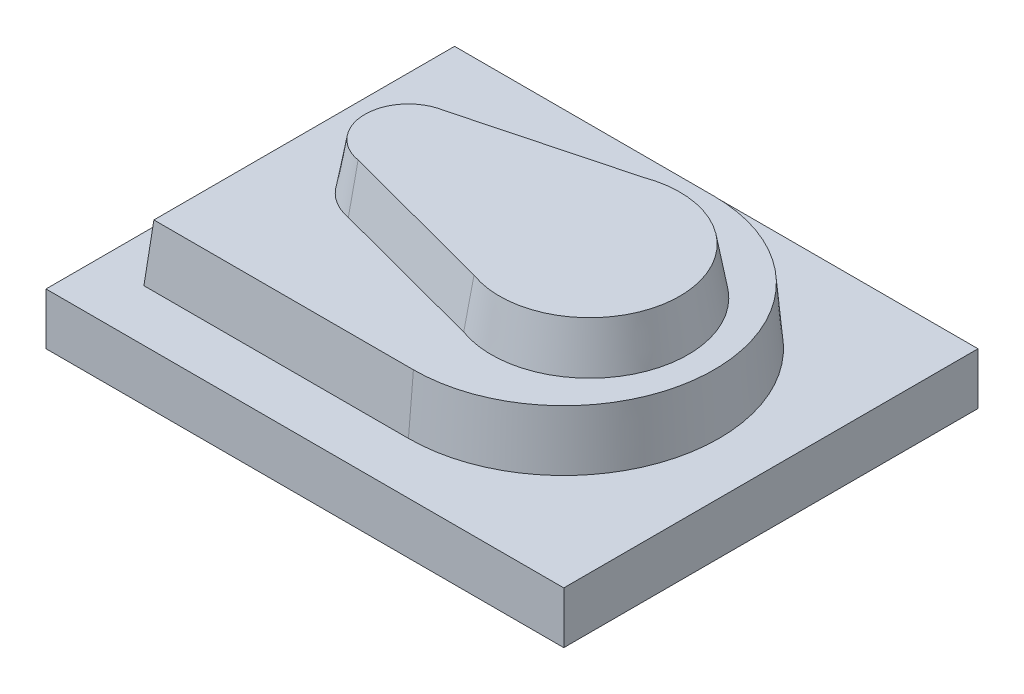
SolidWorks part; units mm, degrees
ref_plane "정면" through (0, 0, 0) normal (0, 0, 1) x (1, 0, 0)
ref_plane "윗면" through (0, 0, 0) normal (0, 1, 0) x (1, 0, 0)
ref_plane "우측면" through (0, 0, 0) normal (1, 0, 0) x (0, 0, -1)
sketch "스케치1" plane through (0, 0, 0) normal (0, 1, 0) x (1, 0, 0)
  line L1 (-50, 40) -> (50, 40)
  line L2 (-50, 40) -> (-50, -40)
  line L3 (-50, -40) -> (50, -40)
  line L4 (50, 40) -> (50, -40)
  line L5 (-50, 40) -> (50, -40) construction
  line L6 (-50, -40) -> (50, 40) construction
  point P0 (0, 0)
  dimension "D1" = 100
  dimension "D2" = 80
extrude "보스-돌출1" add sketch "스케치1" along normal blind 10
sketch "스케치2" plane through (0, 10, 0) normal (0, 1, 0) x (1, 0, 0)
  line L0 (10, 30) -> (-41.0898, 30)
  line L1 (-41.0898, 30) -> (-41.0898, -30)
  line L2 (-41.0898, -30) -> (10, -30)
  line L4 (50, -40) -> (50, 40) construction
  arc A0 (10, 30) -> (10, -30) centre (10, 0) cw
  dimension "D2" = 30
  dimension "D1" = 10
  dimension "D3" = 60
  dimension "D4" = 60
extrude "보스-돌출2" add sketch "스케치2" along normal blind 11 draft 5
ref_plane "평면1" through (0, 21, 0) normal (0, 1, 0) x (1, 0, 0)
sketch "스케치4" plane through (0, 21, 0) normal (0, 1, 0) x (1, 0, 0)
  line L0 (-21.7647, 9.8431) -> (8.5198, 17.8608)
  line L3 (-21.767, -9.8426) -> (8.5427, -17.8691)
  line L4 (-50, 40) -> (-50, -40) construction
  arc A4 (-21.767, -9.8426) -> (-21.7647, 9.8431) centre (-20, 0) cw
  arc A5 (8.5198, 17.8608) -> (8.5427, -17.8691) centre (15, 0) cw
  point P9 (8.5198, -17.8757)
  point P10 (-21.7647, 9.8431)
  point P11 (-21.7647, -9.8426)
  point P12 (8.5198, -17.8691)
  dimension "D1" = 10
  dimension "D2" = 19
  dimension "D3" = 30
  dimension "D4" = 35
extrude "보스-돌출3" add sketch "스케치4" along normal blind 9 draft 10 contours L3 A5 L0 A4
ref_plane "평면3" through (0, 0, 0) normal (0, 0, 1) x (1, 0, 0)
sketch "스케치5" plane through (0, 0, 0) normal (0, 0, 1) x (1, 0, 0)
  arc A0 (-14.7171, 74.7841) -> (32.4131, 30) centre (12.7618, 56.5109) ccw
  point P3 (35.3672, 30)
  point P5 (-23.6151, 45.2895)
  point P6 (39.5666, 30)
  point P7 (24.5188, 30)
  point P8 (32.4131, 30)
  point P10 (-19.473, 63.3049)
  point P11 (-14.7171, 74.7841)
  dimension "D1" = 33
  dimension "D2" = 30
